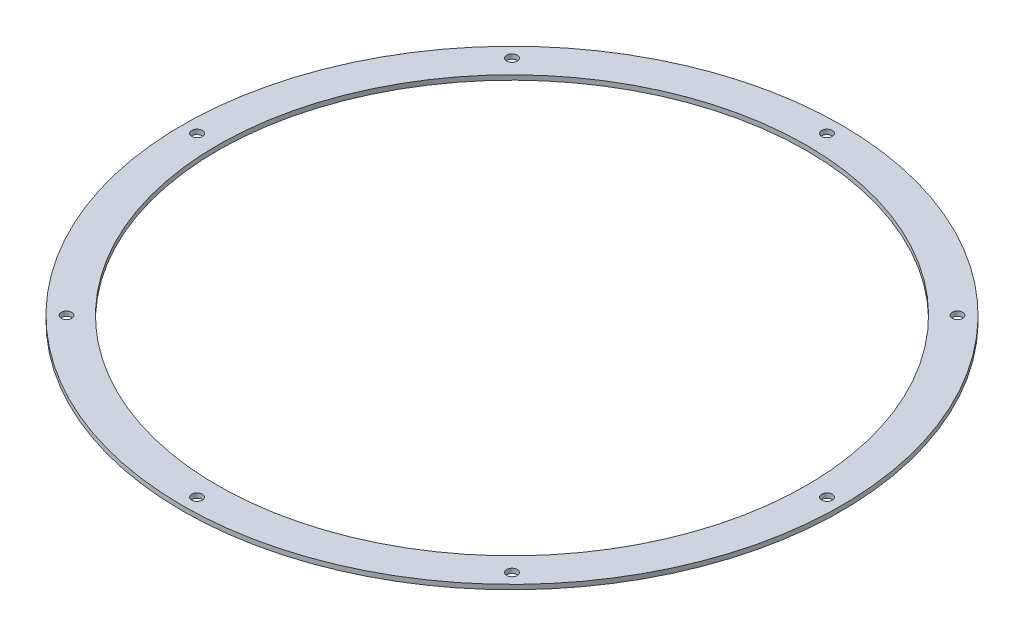
SolidWorks part; units mm, degrees
material "ASTM A36 Steel"
ref_plane "Front Plane" through (0, 0, 0) normal (0, 0, 1) x (1, 0, 0)
ref_plane "Top Plane" through (0, 0, 0) normal (0, 1, 0) x (1, 0, 0)
ref_plane "Right Plane" through (0, 0, 0) normal (1, 0, 0) x (0, 0, -1)
sketch "Sketch1" plane through (0, 0, 0) normal (0, 1, 0) x (1, 0, 0)
  circle A0 centre (0, 0) radius 282.5
  circle A1 centre (0, 0) radius 252.5
  dimension "D1" = 565
  dimension "D2" = 505
extrude "Boss-Extrude1" add sketch "Sketch1" along normal blind 4
sketch "Sketch2" plane through (0, 4, 0) normal (0, 1, 0) x (1, 0, 0)
  line L0 (0, 0) -> (0, 202.3209)
  circle A0 centre (0, 0) radius 270 construction
  circle A1 centre (0, 270) radius 4.5
  dimension "D1" = 540
  dimension "D2" = 9
extrude "Cut-Extrude1" cut sketch "Sketch2" against normal blind 4 contours A0 A1 L0 | L0 A1 A0 | A0 A1 L0 | L0 A1 A0
pattern_circular "CirPattern1" count 8 over 360 about axis through (0, 0, 0) along (0, 1, 0) of "Cut-Extrude1"
